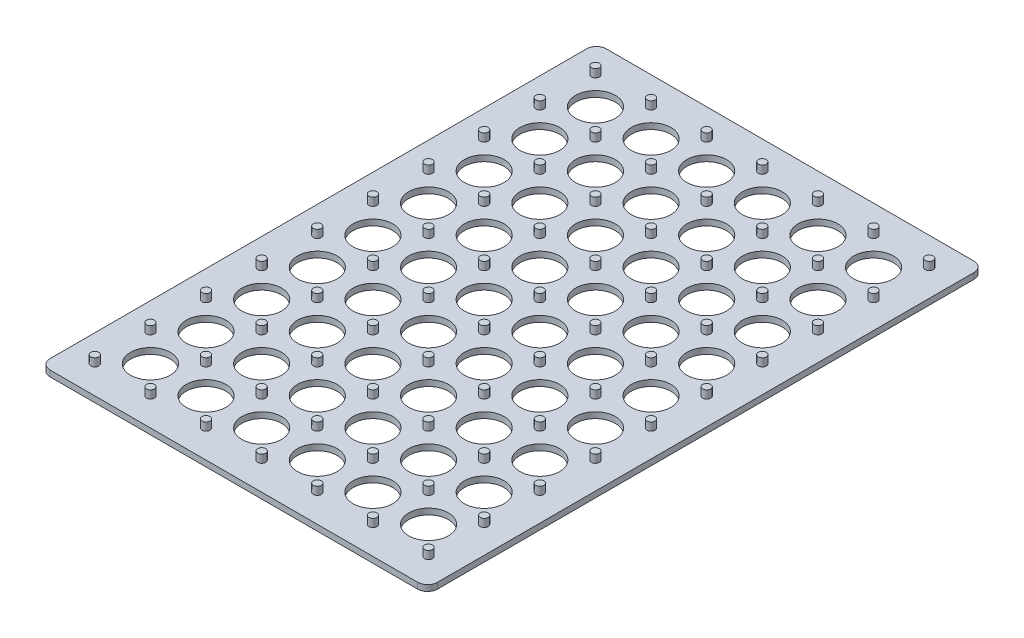
SolidWorks part; units mm, degrees
ref_plane "Спереди" through (0, 0, 0) normal (0, 0, 1) x (1, 0, 0)
ref_plane "Сверху" through (0, 0, 0) normal (0, 1, 0) x (1, 0, 0)
ref_plane "Справа" through (0, 0, 0) normal (1, 0, 0) x (0, 0, -1)
sketch "Эскиз1" plane through (0, 0, 0) normal (0, 1, 0) x (1, 0, 0)
  line L1 (0, 0) -> (195, 0)
  line L2 (0, 0) -> (0, 280)
  line L3 (0, 280) -> (195, 280)
  line L4 (195, 0) -> (195, 280)
  dimension "D1" = 195
  dimension "D2" = 280
extrude "Бобышка-Вытянуть1" add sketch "Эскиз1" along normal blind 3
sketch "Эскиз3" plane through (0, 3, 0) normal (0, 1, 0) x (1, 0, 0)
  line L0 (195, 280) -> (0, 280) construction
  circle A0 centre (97.5, 266) radius 2
  point P4 (97.5, 280)
  dimension "D1" = 4
  dimension "D2" = 14
extrude "Бобышка-Вытянуть2" add sketch "Эскиз3" along normal blind 4
pattern_linear "Линейный массив1" count 4 spacing 28 along (1, 0, 0) count 4 spacing 28 along (-1, 0, 0) of "Бобышка-Вытянуть2"
pattern_linear "Линейный массив2" count 10 spacing 28 along (0, 0, 1) of "Линейный массив1", "Бобышка-Вытянуть2"
sketch "Эскиз4" plane through (0, 3, 0) normal (0, 1, 0) x (1, 0, 0)
  circle A0 centre (111.5, 252) radius 10
  circle A1 centre (97.5, 266) radius 2 construction
  circle A2 centre (125.5, 266) radius 2 construction
  point P4 (0, 0)
  point P6 (122.67, 270.3801)
  dimension "D1" = 20
  dimension "D2" = 14
  dimension "D3" = 14
extrude "Вырез-Вытянуть1" cut sketch "Эскиз4" against normal blind 3
pattern_linear "Линейный массив3" count 3 spacing 28 along (1, 0, 0) count 4 spacing 28 along (-1, 0, 0) of "Вырез-Вытянуть1"
pattern_linear "Линейный массив4" count 9 spacing 28 along (0, 0, 1) of "Линейный массив3", "Вырез-Вытянуть1"
fillet "Скругление1" radius 5 4 edges at (195, 1.5, -280) (0, 1.5, -280) (0, 1.5, 0) (195, 1.5, 0)
